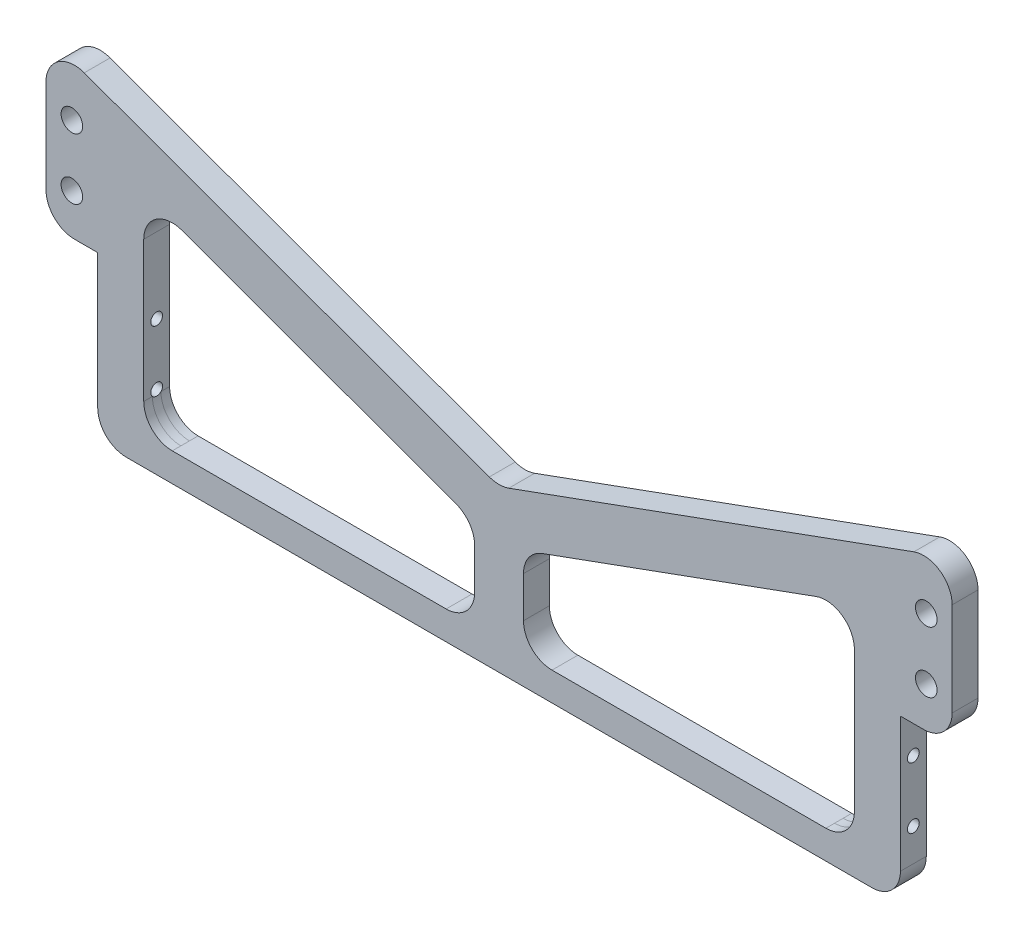
SolidWorks part; units mm, degrees
ref_plane "Front Plane" through (0, 0, 0) normal (0, 0, 1) x (1, 0, 0)
ref_plane "Top Plane" through (0, 0, 0) normal (0, 1, 0) x (1, 0, 0)
ref_plane "Right Plane" through (0, 0, 0) normal (1, 0, 0) x (0, 0, -1)
sketch "Sketch1" plane through (0, 0, 0) normal (0, 0, 1) x (1, 0, 0)
  line L1 (-111.25, -40) -> (111.25, -40)
  line L2 (-111.25, -40) -> (-111.25, 40)
  line L3 (-111.25, 40) -> (111.25, 40)
  line L4 (111.25, -40) -> (111.25, 40)
  line L5 (-111.25, -40) -> (111.25, 40) construction
  line L6 (-111.25, 40) -> (111.25, -40) construction
  point P0 (0, 0)
  dimension "D1" = 222.5
  dimension "D2" = 80
extrude "Boss-Extrude1" add sketch "Sketch1" along normal blind 6.35
sketch "Sketch6" plane through (-111.25, 0, 0) normal (-1, 0, 0) x (0, 0, 1)
  line L0 (6.35, 40) -> (6.35, -40) construction
  line L1 (0, -40) -> (6.35, -40)
  line L2 (0, -40) -> (0, 0)
  line L3 (0, 0) -> (6.35, 0)
  line L4 (6.35, -40) -> (6.35, 0)
extrude "Cut-Extrude3" cut sketch "Sketch6" against normal blind 12.7
hole_wizard "M3.5x0.6 Tapped Hole1" positions "Sketch8" profile "Sketch7" tap size "M3.5x0.6" standard "ANSI Metric"
sketch "Sketch8" plane through (-98.55, 0, 0) normal (-1, 0, 0) x (0, 0, 1)
  line L0 (3.175, -40) -> (3.175, 0) construction
  line L1 (0, -40) -> (6.35, -40) construction
  line L2 (6.35, 0) -> (0, 0) construction
  point P9 (3.175, -25)
  point P11 (3.175, -10)
  dimension "D1" = 15
  dimension "D2" = 15
sketch "Sketch7" plane through (-98.55, -25, 3.175) normal (0, 1, 0) x (0, 0, 1)
  line L0 (0, 0) -> (0, 14.6712)
  line L1 (0, 14.6712) -> (1.45, 13.8)
  line L2 (1.45, 13.8) -> (1.45, 0)
  line L5 (1.45, 0) -> (0, 0)
  line L10 (0, 14.6712) -> (-1.45, 13.8) construction
  line L11 (0, -6.35) -> (0, 107.95) construction
  dimension "Tap Drill Dia." = 2.9
  dimension "Tap Drill Depth" = 13.8
  dimension "Drill Angle" = 118
cosmetic thread "Hole Thread3"
cosmetic thread "Hole Thread4"
sketch "Sketch2" plane through (0, 0, 6.35) normal (0, 0, 1) x (1, 0, 0)
  line L0 (111.25, 40) -> (0, -0.4917)
  line L1 (0, -0.4917) -> (-111.25, 40)
  line L2 (-111.25, 40) -> (111.25, 40)
  line L3 (0, 18.416) -> (0, 40) construction
  line L6 (111.25, 40) -> (-111.25, 40) construction
  dimension "D1" = 20
extrude "Cut-Extrude1" cut sketch "Sketch2" against normal through all
sketch "Sketch3" plane through (0, 0, 6.35) normal (0, 0, 1) x (1, 0, 0)
  line L0 (-87.25, -33) -> (-87.25, 18.4946)
  line L1 (-87.25, 18.4946) -> (-6, -11.078)
  line L2 (-6, -11.078) -> (-6, -33)
  line L3 (-6, -33) -> (-87.25, -33)
  line L4 (0, -0.4917) -> (0, 56.2405) construction
  line L5 (111.25, 40) -> (111.25, -40) construction
  line L6 (-98.55, -40) -> (111.25, -40) construction
  line L8 (-111.25, 0) -> (-111.25, 40) construction
  line L9 (0, -0.4917) -> (-111.25, 40) construction
  dimension "D1" = 12
  dimension "D2" = 12
  dimension "D3" = 7
  dimension "D4" = 24
extrude "Cut-Extrude2" cut sketch "Sketch3" against normal through all
hole_wizard "M5 Clearance Hole1" positions "Sketch5" profile "Sketch4" hole size "M5" standard "ANSI Metric" end condition through all
sketch "Sketch5" plane through (0, 0, 0) normal (0, 0, -1) x (-1, 0, 0)
  line L0 (104.9, 52.8471) -> (104.9, -49.7544) construction
  line L6 (111.25, 0) -> (111.25, 40) construction
  point P27 (104.9, 10)
  point P29 (104.9, 25)
  dimension "D1" = 6.35
  dimension "D2" = 15
  dimension "D3" = 15
sketch "Sketch4" plane through (-104.9, 10, 0) normal (1, 0, 0) x (0, 1, 0)
  line L0 (0, 0) -> (0, 6.35)
  line L1 (0, 6.35) -> (2.65, 6.35)
  line L2 (2.65, 6.35) -> (2.65, 0)
  line L5 (2.65, 0) -> (0, 0)
  line L11 (0, -6.35) -> (0, 107.95) construction
  dimension "Thru Hole Dia." = 5.3
  dimension "Thru Hole Depth" = 6.35
mirror "Mirror1" about plane through (0, 0, 0) normal (1, 0, 0) of "M3.5x0.6 Tapped Hole1", "M5 Clearance Hole1", "Cut-Extrude2", "Cut-Extrude3"
fillet "Fillet1" radius 7 15 edges at (6, -11.078, 3.175) (87.25, 18.4946, 3.175) (-6, -11.078, 3.175) (-6, -33, 3.175) (87.25, -33, 3.175) (6, -33, 3.175) (-87.25, -33, 3.175) (111.25, 40, 3.175) (0, -0.4917, 3.175) (-111.25, 40, 3.175) (-87.25, 18.4946, 3.175) (111.25, 0, 3.175) (98.55, -40, 3.175) (-98.55, -40, 3.175) (-111.25, 0, 3.175)
